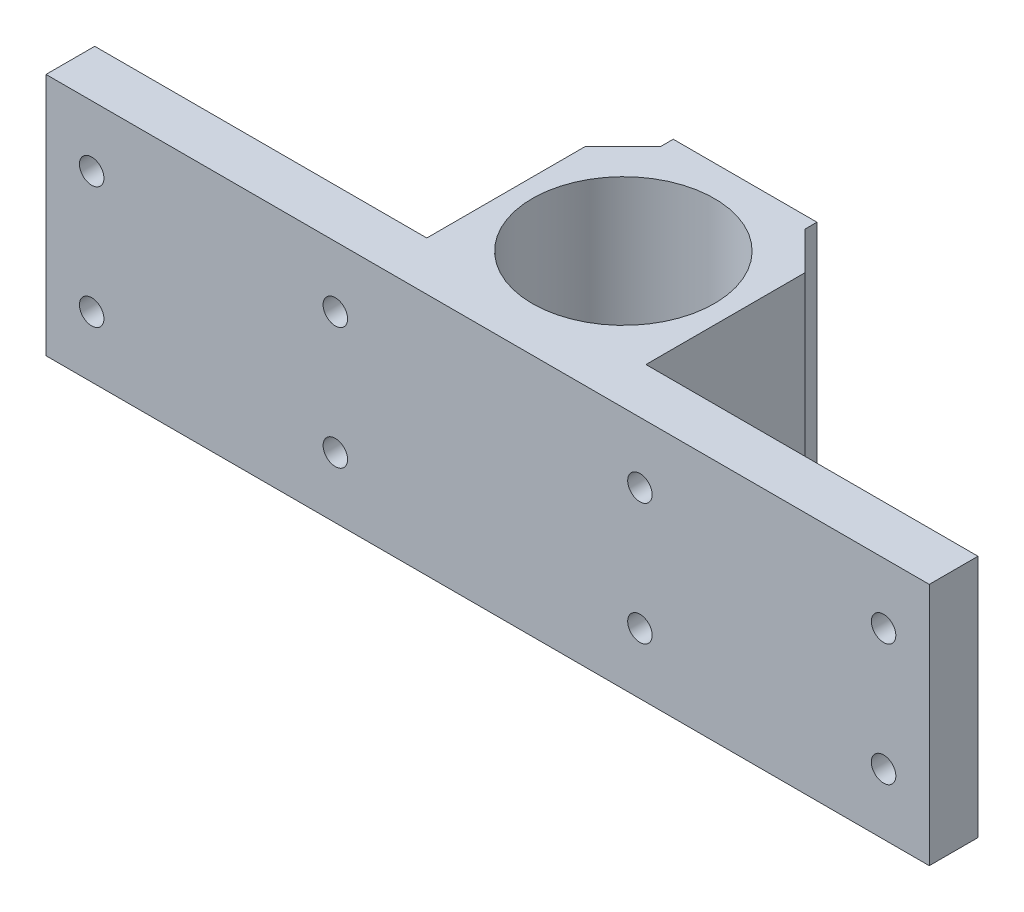
SolidWorks part; units mm, degrees
ref_plane "Front Plane" through (0, 0, 0) normal (0, 0, 1) x (1, 0, 0)
ref_plane "Top Plane" through (0, 0, 0) normal (0, 1, 0) x (1, 0, 0)
ref_plane "Right Plane" through (0, 0, 0) normal (1, 0, 0) x (0, 0, -1)
sketch "Sketch1" plane through (0, 0, 0) normal (0, 0, 1) x (1, 0, 0)
  line L1 (-87.7906, 21.747) -> (96.3594, 21.747)
  line L2 (-87.7906, 21.747) -> (-87.7906, -29.053)
  line L3 (-87.7906, -29.053) -> (96.3594, -29.053)
  line L4 (96.3594, 21.747) -> (96.3594, -29.053)
  dimension "D1" = 184.15
  dimension "D2" = 50.8
extrude "Boss-Extrude1" add sketch "Sketch1" along normal blind 10.16
sketch "Sketch5" plane through (0, 21.747, 0) normal (0, 1, 0) x (1, 0, 0)
  line L0 (10.8884, 0) -> (10.8884, -10.16)
  line L1 (96.3594, 0) -> (-87.7906, 0) construction
  line L2 (96.3594, -10.16) -> (-87.7906, -10.16) construction
  line L3 (-2.3196, 0) -> (-2.3196, -10.16)
  point P8 (4.2844, 0)
  dimension "D1" = 6.604
  dimension "D2" = 6.604
sketch "Sketch6" plane through (0, 21.747, 0) normal (0, 1, 0) x (1, 0, 0)
  arc A0 (10.8884, 0) -> (-2.3196, 0) centre (4.2844, 10.8827) cw
extrude "Cut-Extrude1" cut sketch "Sketch6" against normal through all and the other way through all flip side to cut
sketch "Sketch7" plane through (0, 21.747, 0) normal (0, 1, 0) x (1, 0, 0)
  line L0 (4.2844, -4.7215) -> (4.2844, 18.1385)
  line L1 (-87.7906, -10.16) -> (-87.7906, 0) construction
  circle A1 centre (4.2844, 18.1385) radius 22.8473
  dimension "D1" = 22.86
  dimension "D2" = 92.075
extrude "Boss-Extrude2" add sketch "Sketch7" against normal through all contours A1
sketch "Sketch8" plane through (0, 21.747, 0) normal (0, 1, 0) x (1, 0, 0)
  circle A0 centre (4.2844, 18.1385) radius 18.9865
  dimension "D1" = 37.973
extrude "Cut-Extrude2" cut sketch "Sketch8" against normal blind 45.72
sketch "Sketch9" plane through (0, -23.973, 0) normal (0, 1, 0) x (1, 0, 0)
  circle A0 centre (4.2844, 18.1385) radius 7.9375
  circle A1 centre (4.2844, 18.1385) radius 18.9865 construction
  dimension "D1" = 15.875
  dimension "D2" = 0
extrude "Cut-Extrude3" cut sketch "Sketch9" against normal through all
sketch "Sketch12" plane through (0, 21.747, 0) normal (0, 1, 0) x (1, 0, 0)
  line L0 (27.1317, 18.1385) -> (27.1317, 0)
  line L1 (96.3594, 0) -> (18.1766, 0) construction
  line L2 (27.1317, 0) -> (18.1766, 0)
  line L3 (-18.5629, 18.1385) -> (-18.5629, 0)
  line L4 (-9.6078, 0) -> (-87.7906, 0) construction
  line L5 (-18.5629, 0) -> (-9.6078, 0)
  circle A0 centre (4.2844, 18.1385) radius 22.8473 construction
  arc A1 (18.1766, 0) -> (27.1317, 18.1385) centre (4.2844, 18.1385) ccw
  arc A2 (-9.6078, 0) -> (-18.5629, 18.1385) centre (4.2844, 18.1385) cw
extrude "Boss-Extrude3" add sketch "Sketch12" against normal up to surface (50.8 mm away) up to face at (4.2844, -29.053, -10.201)
sketch "Sketch16" plane through (0, -29.053, 0) normal (0, -1, 0) x (1, 0, 0)
  line L0 (-18.5629, -18.1385) -> (-18.5629, -40.9857)
  line L1 (4.2844, -40.9857) -> (-18.5629, -40.9857)
  arc A0 (-18.5629, -18.1385) -> (27.1317, -18.1385) centre (4.2844, -18.1385) ccw construction
  arc A1 (-18.5629, -18.1385) -> (4.2844, -40.9857) centre (4.2844, -18.1385) ccw
extrude "Boss-Extrude4" add sketch "Sketch16" against normal up to surface (50.8 mm away) up to face at (4.2844, 21.747, -4.8505)
sketch "Sketch18" plane through (0, -29.053, 0) normal (0, -1, 0) x (1, 0, 0)
  line L0 (27.1317, -18.1385) -> (27.1317, -40.9857)
  line L1 (27.1317, -40.9857) -> (4.2844, -40.9857)
  arc A0 (27.1317, -18.1385) -> (4.2844, -40.9857) centre (4.2844, -18.1385) cw
extrude "Boss-Extrude5" add sketch "Sketch18" against normal up to surface (50.8 mm away) up to face at (4.8102, 21.747, -9.3913)
sketch "Sketch19" plane through (0, 21.747, 0) normal (0, 1, 0) x (1, 0, 0)
  line L2 (27.1317, 40.9857) -> (-18.5629, 40.9857) construction
  line L3 (19.2577, 40.9857) -> (27.1317, 40.9857)
  line L6 (-18.5629, 40.9857) -> (-18.5629, 0) construction
  line L8 (-18.5629, 40.9857) -> (-18.5629, 33.1259)
  line L9 (-18.5629, 33.1259) -> (-10.703, 40.9857)
  line L10 (-10.703, 40.9857) -> (-18.5629, 40.9857)
  line L11 (19.2577, 40.9857) -> (27.1317, 33.1117)
  line L12 (27.1317, 0) -> (27.1317, 40.9857) construction
  line L13 (27.1317, 33.1117) -> (27.1317, 40.9857)
  dimension "D1" = 7.8599
  dimension "D2" = 7.874
extrude "Cut-Extrude6" cut sketch "Sketch19" against normal through all
hole_wizard "#10 Clearance Hole1" positions "Sketch23" profile "Sketch24" hole size "#10" standard "ANSI Inch" end condition through all
sketch "Sketch23" plane through (0, 0, 0) normal (0, 0, -1) x (-1, 0, 0)
  line L0 (87.7906, 21.747) -> (87.7906, -29.053) construction
  line L1 (87.7906, -29.053) -> (18.5629, -29.053) construction
  line L2 (18.5629, 21.747) -> (87.7906, 21.747) construction
  line L3 (-96.3594, -29.053) -> (-96.3594, 21.747) construction
  line L4 (-96.3594, 21.747) -> (-27.1317, 21.747) construction
  line L5 (-27.1317, -29.053) -> (-96.3594, -29.053) construction
  point P0 (78.2656, 9.047)
  point P2 (78.2656, -16.353)
  point P4 (-86.8344, -16.353)
  point P6 (-86.8344, 9.047)
  dimension "D1" = 9.525
  dimension "D2" = 12.7
  dimension "D3" = 12.7
  dimension "D4" = 9.525
  dimension "D5" = 9.525
  dimension "D6" = 12.7
  dimension "D7" = 12.7
  dimension "D8" = 9.525
sketch "Sketch24" plane through (-78.2656, 9.047, 0) normal (1, 0, 0) x (0, 1, 0)
  line L0 (0, 0) -> (0, 10.16)
  line L1 (0, 10.16) -> (2.5527, 10.16)
  line L2 (2.5527, 10.16) -> (2.5527, 0)
  line L5 (2.5527, 0) -> (0, 0)
  line L11 (0, -6.35) -> (0, 107.95) construction
  dimension "Thru Hole Dia." = 5.1054
  dimension "Thru Hole Depth" = 10.16
hole_wizard "#10 Clearance Hole2" positions "Sketch25" profile "Sketch26" hole size "#10" standard "ANSI Inch" end condition through all
sketch "Sketch25" plane through (0, 0, 0) normal (0, 0, -1) x (-1, 0, 0)
  line L0 (87.7906, -29.053) -> (18.5629, -29.053) construction
  line L2 (18.5629, 21.747) -> (87.7906, 21.747) construction
  line L3 (-96.3594, 21.747) -> (-27.1317, 21.747) construction
  line L5 (-27.1317, -29.053) -> (-96.3594, -29.053) construction
  circle A0 centre (78.2656, -16.353) radius 2.5527 construction
  circle A1 centre (78.2656, 9.047) radius 2.5527 construction
  circle A2 centre (-86.8344, 9.047) radius 2.5527 construction
  circle A3 centre (-86.8344, -16.353) radius 2.5527 construction
  point P0 (27.4656, -16.353)
  point P2 (27.4656, 9.047)
  point P4 (-36.0344, 9.047)
  point P6 (-36.0344, -16.353)
  dimension "D1" = 12.7
  dimension "D2" = 50.8
  dimension "D3" = 50.8
  dimension "D4" = 12.7
  dimension "D5" = 12.7
  dimension "D6" = 50.8
  dimension "D7" = 50.8
  dimension "D8" = 12.7
sketch "Sketch26" plane through (-27.4656, -16.353, 0) normal (1, 0, 0) x (0, 1, 0)
  line L0 (0, 0) -> (0, 10.16)
  line L1 (0, 10.16) -> (2.5527, 10.16)
  line L2 (2.5527, 10.16) -> (2.5527, 0)
  line L5 (2.5527, 0) -> (0, 0)
  line L11 (0, -6.35) -> (0, 107.95) construction
  dimension "Thru Hole Dia." = 5.1054
  dimension "Thru Hole Depth" = 10.16
sketch "Sketch31" plane through (0, 0, -40.9857) normal (0, 0, -1) x (-1, 0, 0)
  line L1 (-19.2577, -29.053) -> (10.703, -29.053)
  line L2 (-19.2577, -29.053) -> (-19.2577, 21.747)
  line L3 (-19.2577, 21.747) -> (10.703, 21.747)
  line L4 (10.703, -29.053) -> (10.703, 21.747)
extrude "Boss-Extrude6" add sketch "Sketch31" along normal blind 2.54
hole_wizard "3/16 (0.1875) Diameter Hole3" positions "Sketch32" profile "Sketch33" hole size "3/16" standard "ANSI Inch"
sketch "Sketch32" plane through (-25.8444, 0, -25.8444) normal (-0.7071, 0, -0.7071) x (-0.7071, 0, 0.7071)
  line L0 (-10.2976, -29.053) -> (-21.4131, -29.053) construction
  line L1 (-10.2976, -29.053) -> (-10.2976, 21.747) construction
  point P0 (-15.3776, -20.163)
  point P2 (-15.3776, -7.463)
  dimension "D1" = 8.89
  dimension "D2" = 12.7
  dimension "D3" = 5.08
sketch "Sketch33" plane through (-14.9708, -20.163, -36.718) normal (0, 1, 0) x (-0.7071, 0, 0.7071)
  line L0 (0, 0) -> (0, 7.7726)
  line L1 (0, 7.7726) -> (2.3812, 7.7726)
  line L2 (2.3812, 7.7726) -> (2.3812, 0)
  line L5 (2.3812, 0) -> (0, 0)
  line L11 (0, -6.35) -> (0, 107.95) construction
  dimension "Thru Hole Dia." = 4.7625
  dimension "Thru Hole Depth" = 7.7726
hole_wizard "3/16 (0.1875) Diameter Hole4" positions "Sketch34" profile "Sketch35" hole size "3/16" standard "ANSI Inch"
sketch "Sketch34" plane through (30.1217, 0, -30.1217) normal (0.7071, 0, -0.7071) x (-0.7071, 0, -0.7071)
  line L0 (15.3641, -29.053) -> (4.2285, -29.053) construction
  line L1 (4.2285, -29.053) -> (4.2285, 21.747) construction
  point P0 (9.3085, -20.163)
  point P2 (9.3085, -7.463)
  dimension "D1" = 8.89
  dimension "D2" = 12.7
  dimension "D3" = 5.08
sketch "Sketch35" plane through (23.5395, -20.163, -36.7038) normal (0, 1, 0) x (-0.7071, 0, -0.7071)
  line L0 (0, 0) -> (0, 7.7629)
  line L1 (0, 7.7629) -> (2.3812, 7.7629)
  line L2 (2.3812, 7.7629) -> (2.3812, 0)
  line L5 (2.3812, 0) -> (0, 0)
  line L11 (0, -6.35) -> (0, 107.95) construction
  dimension "Thru Hole Dia." = 4.7625
  dimension "Thru Hole Depth" = 7.7629
